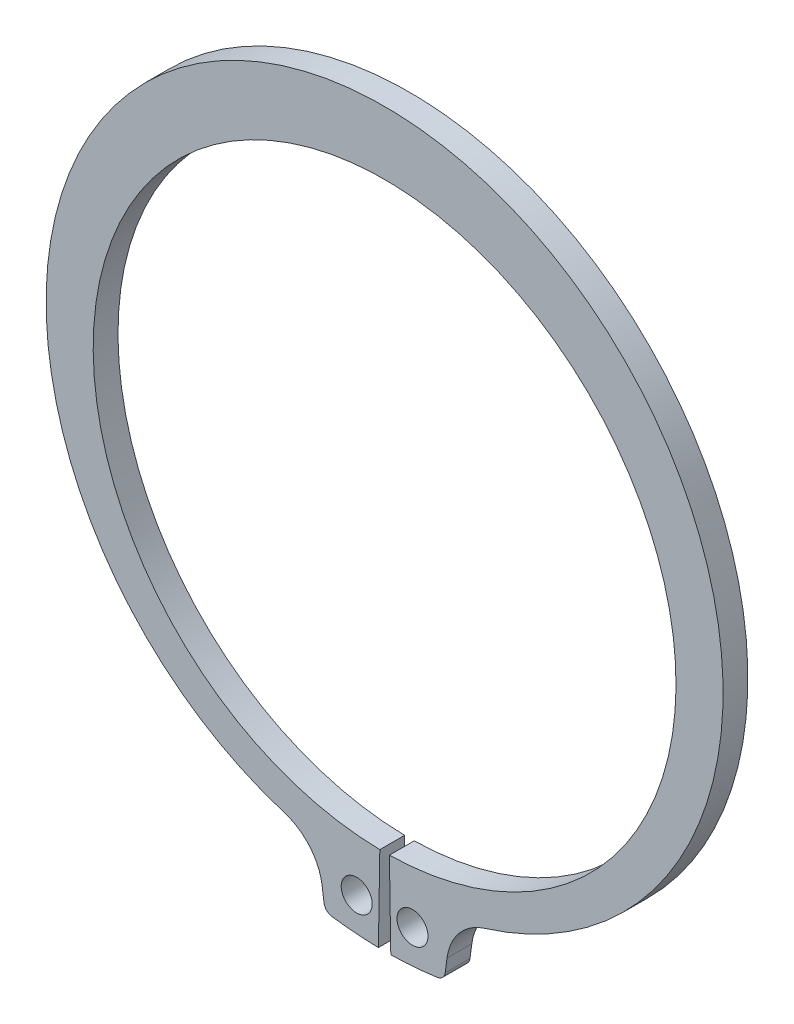
SolidWorks part; units mm, degrees
ref_plane "Plane1" through (0, 0, 0) normal (0, 0, 1) x (1, 0, 0)
ref_plane "Plane2" through (0, 0, 0) normal (0, 1, 0) x (1, 0, 0)
ref_plane "Plane3" through (0, 0, 0) normal (1, 0, 0) x (0, 0, -1)
sketch "Clipboard" plane through (0, 0, 0) normal (0, 0, 1) x (1, 0, 0)
  line L0 (0, 0) -> (5.1, 0)
  line L1 (0, 0) -> (0, 2.55)
  line L2 (0, 0) -> (0, -6.9)
  circle A0 centre (0, 0) radius 1.25
  circle A1 centre (0, 0) radius 25
  dimension "HoleDia" = 2.5
  dimension "ShaftDia" = 50
  dimension "LargeSection" = 5.1
  dimension "SmallSection" = 2.55
  dimension "LugSection" = 6.9
sketch "BodySke" plane through (0, 0, 0) normal (0, 0, 1) x (1, 0, 0)
  line L0 (-1.5431, 0) -> (1.5431, 0) construction
  line L1 (0, 0) -> (0, 28.6) construction
  line L2 (0.3865, -23.4968) -> (0.5, -30.3959)
  line L3 (-0.3865, -23.4968) -> (-0.5, -30.3959)
  line L4 (0, 0) -> (9.3453, -28.9279) construction
  line L5 (0, 0) -> (-9.3453, -28.9279) construction
  line L7 (5.0329, -28.3602) -> (4.8885, -29.4567)
  line L8 (-5.0329, -28.3602) -> (-4.8885, -29.4567)
  circle A0 centre (0, 0) radius 23.5 construction
  arc A1 (0.3865, -23.4968) -> (-0.3865, -23.4968) centre (0, 0) ccw
  arc A2 (8.008, -24.7886) -> (-8.008, -24.7886) centre (0, 1.3051) ccw construction
  arc A3 (0.5, -30.3959) -> (4.2498, -30.1015) centre (0, 0) ccw
  arc A4 (8.0607, -24.7724) -> (5.0329, -28.3602) centre (9.3453, -28.9279) ccw
  arc A5 (-5.0329, -28.3602) -> (-8.0607, -24.7724) centre (-9.3453, -28.9279) ccw
  arc A6 (-4.2498, -30.1015) -> (-0.5, -30.3959) centre (0, 0) ccw
  arc A7 (8.0607, -24.7724) -> (-8.0607, -24.7724) centre (0, 1.3051) ccw
  arc A8 (-5.1842, -27.2105) -> (5.1842, -27.2105) centre (0, 0) ccw construction
  circle A9 centre (2.25, -27.6085) radius 1.25
  circle A10 centre (-2.25, -27.6085) radius 1.25
  arc A11 (4.8885, -29.4567) -> (4.2498, -30.1015) centre (4.1449, -29.3589) cw
  arc A12 (-4.8885, -29.4567) -> (-4.2498, -30.1015) centre (-4.1449, -29.3589) ccw
  point P28 (4.8148, -30.0163)
  point P31 (-4.8148, -30.0163)
  dimension "HoleDia" = 2.5
  dimension "GrooveDia" = 47
  dimension "LugRad" = 30.4
  dimension "HoleOffsetRad" = 27.7
  dimension "D3" = 0.75
  dimension "LargeRad" = 28.6
  dimension "SmallRad" = 26.05
  dimension "SmallAngle" = 35.806
  dimension "D2" = 15
  dimension "HoleSpacing" = 4.5
  dimension "Gap" = 1
extrude "Body" add sketch "BodySke" against normal blind 2
sketch "NotSke" plane through (0, 0, 0) normal (0, 0, 1) x (1, 0, 0)
  line L0 (2.25, -26.3585) -> (2.25, -28.8585)
  line L1 (2.25, -28.8585) -> (-2.25, -28.8585)
  line L2 (-2.25, -28.8585) -> (-2.25, -26.3585)
  line L3 (-2.25, -26.3585) -> (2.25, -26.3585)
  circle A0 centre (2.25, -27.6085) radius 1.25 construction
  circle A1 centre (-2.25, -27.6085) radius 1.25 construction
extrude "Notch" [suppressed] cut sketch "NotSke" against normal through all
sketch "UnlSke" plane through (0, 0, 0) normal (0, 0, 1) x (1, 0, 0)
  line L0 (-3.8341, -30.1572) -> (-2.9639, -23.3123)
  line L1 (3.8341, -30.1572) -> (2.9639, -23.3123)
  arc A0 (2.9639, -23.3123) -> (-2.9639, -23.3123) centre (0, 0) ccw
  arc A1 (3.8341, -30.1572) -> (-3.8341, -30.1572) centre (0, 0) ccw
  arc A2 (0.5, -30.3959) -> (4.2498, -30.1015) centre (0, 0) ccw construction
  arc A3 (0.3865, -23.4968) -> (-0.3865, -23.4968) centre (0, 0) ccw construction
  circle A4 centre (-2.25, -27.6085) radius 1.25 construction
  circle A5 centre (2.25, -27.6085) radius 1.25 construction
extrude "Unlug" [suppressed] add sketch "UnlSke" against normal through all
equation "' \"ShaftDia@Clipboard\" = 3"
equation "' \"Thickness@Body\" = 0.4"
equation "' \"GrooveDia@BodySke\" = 2.8"
equation "' \"LugSection@Clipboard\" = 1.9"
equation "' \"LargeSection@Clipboard\" = 0.8"
equation "' \"HoleDia@Clipboard\" = 1.0"
equation "' \"ShaftDia@Clipboard\" = 10"
equation "' \"Thickness@Body\" = 1.0"
equation "' \"GrooveDia@BodySke\" = 9.6"
equation "' \"LugSection@Clipboard\" = 3.3"
equation "' \"LargeSection@Clipboard\" = 1.8"
equation "' \"HoleDia@Clipboard\" = 1.5"
equation "\"SmallSection@Clipboard\" = \"LargeSection@Clipboard\" * 0.5"
equation "\"Gap@BodySke\" =  \"Thickness@Body\" / 2"
equation "\"LargeRad@BodySke\" =  \"GrooveDia@BodySke\" / 2 +  \"LargeSection@Clipboard\""
equation "\"SmallRad@BodySke\" =  \"GrooveDia@BodySke\" / 2 +  \"SmallSection@Clipboard\""
equation "\"LugRad@BodySke\" = \"GrooveDia@BodySke\" / 2 + \"LugSection@Clipboard\""
equation "\"HoleOffsetRad@BodySke\" = (  \"ShaftDia@Clipboard\" / 2 + \"LugRad@BodySke\" ) / 2"
equation "\"HoleSpacing@BodySke\" = \"Gap@BodySke\"  * 2 +  \"HoleDia@Clipboard\""
equation "\"HoleDia@BodySke\" =  \"HoleDia@Clipboard\""
equation "\"SmallAngle@BodySke\" = atn(\"HoleSpacing@BodySke\" / 2 / sqr(\"HoleOffsetRad@BodySke\"  * \"HoleOffsetRad@BodySke\" - (\"HoleSpacing@BodySke\" / 2) * (\"HoleSpacing@BodySke\" / 2) ))  * 7 *  (\"LargeRad@BodySke\" / \"SmallRad@BodySke\")* ( 180 / 3.141593)"
